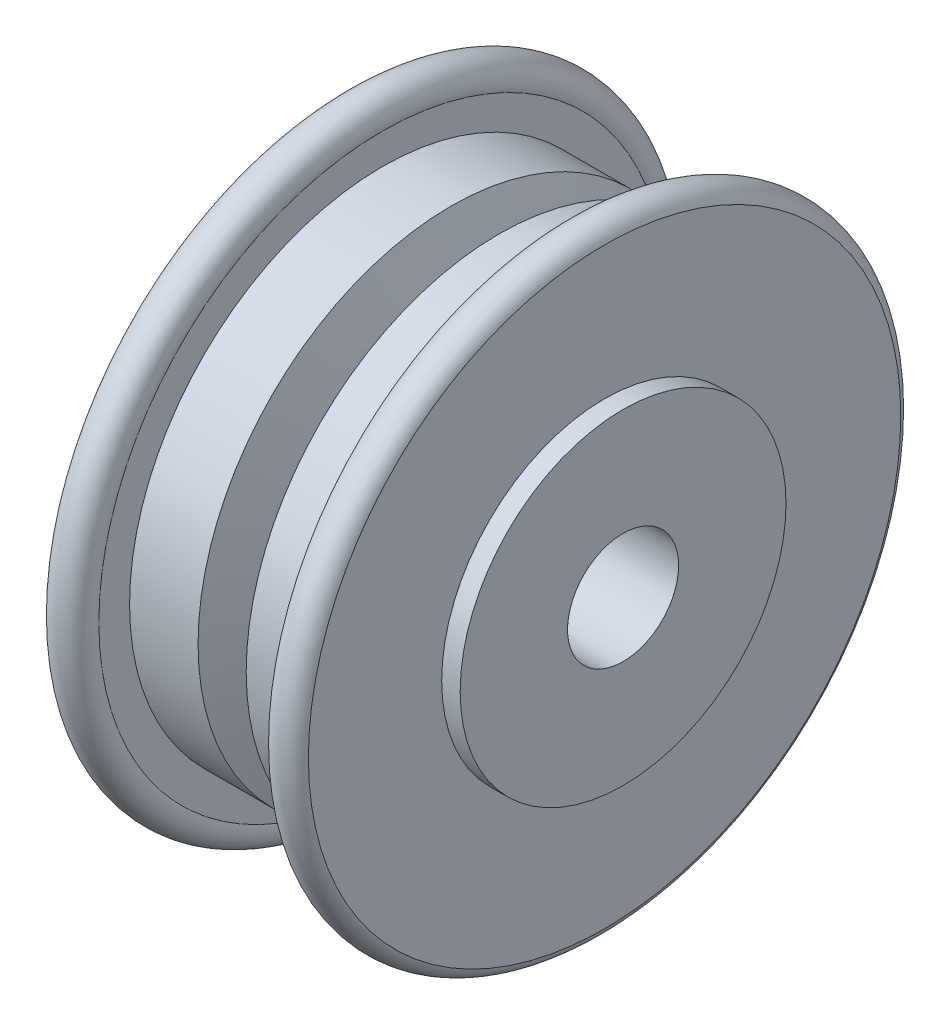
SolidWorks part; units mm, degrees
ref_plane "Front Plane" through (0, 0, 0) normal (0, 0, 1) x (1, 0, 0)
ref_plane "Top Plane" through (0, 0, 0) normal (0, 1, 0) x (1, 0, 0)
ref_plane "Right Plane" through (0, 0, 0) normal (1, 0, 0) x (0, 0, -1)
sketch "Sketch1" plane through (0, 0, 0) normal (0, 0, 1) x (1, 0, 0)
  line L0 (0, 0) -> (135637.0918, 0) construction
  line L1 (0, 0) -> (0, -135637.0918) construction
  line L2 (-5, 160) -> (-5, 0)
  line L3 (5, 88) -> (-5, 88)
  line L4 (5, 88) -> (5, 0)
  line L6 (-5, 88) -> (-5, 0)
  line L7 (5, 88) -> (-5, -88) construction
  line L8 (5, -88) -> (-5, 88) construction
  line L10 (-25, -160) -> (-25, -143.4036)
  line L12 (-25, 136.5964) -> (-25, 0)
  line L14 (-62, 0) -> (-62, 136.5964)
  line L15 (-62, 136.5964) -> (-25, 136.5964)
  line L16 (-62, 136.5964) -> (-75, 98.2753)
  line L17 (-25, 0) -> (-25, 153.1928)
  line L18 (-75, 286.8389) -> (-75, -286.8389) construction
  line L19 (-155, 0) -> (5, 0)
  line L22 (-155, 88) -> (-155, 0)
  line L23 (-155, 88) -> (-145, 88)
  line L24 (-145, 160) -> (-145, 0)
  line L26 (-88, 136.5964) -> (-125, 136.5964)
  line L27 (-88, 0) -> (-88, 136.5964)
  line L28 (-88, 136.5964) -> (-75, 98.2753)
  line L30 (-125, 0) -> (-125, 153.1928)
  arc A0 (-5, 160) -> (-25, 153.1928) centre (-15, 156.5964) ccw
  arc A3 (-145, 160) -> (-125, 153.1928) centre (-135, 156.5964) cw
  point P5 (0, 0)
  point P13 (-5, 0)
  point P20 (-25, -3.4036)
  point P27 (-75, 0)
  dimension "D5" = 37
  dimension "D1" = 176
  dimension "D2" = 10
  dimension "D4" = 20
  dimension "D6" = 13
revolve "Revolve9" add sketch "Sketch1" angle 360 about L0
sketch "Sketch2" plane through (5, 0, 0) normal (1, 0, 0) x (0, 0, -1)
  circle A0 centre (0, 0) radius 30
extrude "Cut-Extrude1" cut sketch "Sketch2" against normal blind 500
